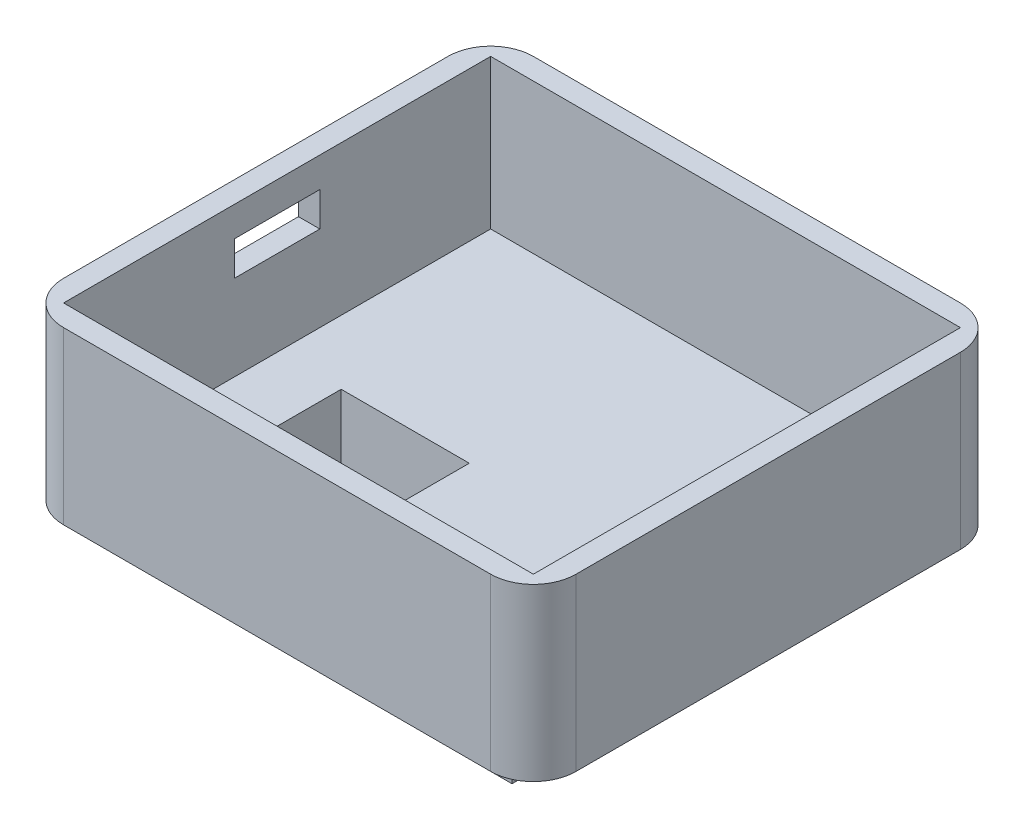
SolidWorks part; units mm, degrees
ref_plane "Front Plane" through (0, 0, 0) normal (0, 0, 1) x (1, 0, 0)
ref_plane "Top Plane" through (0, 0, 0) normal (0, 1, 0) x (1, 0, 0)
ref_plane "Right Plane" through (0, 0, 0) normal (1, 0, 0) x (0, 0, -1)
sketch "Sketch5" plane through (0, 0, 0) normal (0, 1, 0) x (1, 0, 0)
  line L0 (-30, 27.5) -> (30, -27.5) construction
  line L1 (-30, 27.5) -> (30, 27.5)
  line L2 (-30, 27.5) -> (-30, -27.5)
  line L3 (-30, -27.5) -> (30, -27.5)
  line L4 (30, 27.5) -> (30, -27.5)
  line L5 (30, 27.5) -> (-30, -27.5) construction
  point P4 (0, 0)
  dimension "D1" = 60
  dimension "D2" = 55
extrude "Boss-Extrude4" add sketch "Sketch5" along normal blind 20
sketch "Sketch6" plane through (0, 20, 0) normal (0, 1, 0) x (1, 0, 0)
  line L0 (-27.5, 25) -> (27.5, -25) construction
  line L1 (-27.5, 25) -> (27.5, 25)
  line L2 (-27.5, 25) -> (-27.5, -25)
  line L3 (-27.5, -25) -> (27.5, -25)
  line L4 (27.5, 25) -> (27.5, -25)
  line L5 (-27.5, -25) -> (27.5, 25) construction
  point P4 (0, 0)
  dimension "D1" = 55
  dimension "D2" = 50
extrude "Cut-Extrude2" cut sketch "Sketch6" against normal blind 17.5
fillet "Fillet1" radius 5 4 edges at (-30, 10, 27.5) (-30, 10, -27.5) (30, 10, -27.5) (30, 10, 27.5)
sketch "Sketch8" plane through (0, 0, 0) normal (0, -1, 0) x (1, 0, 0)
  line L0 (-22.5, 22.5) -> (22.5, -22.5) construction
  line L1 (-22.5, 22.5) -> (22.5, 22.5)
  line L2 (-22.5, 22.5) -> (-22.5, -22.5)
  line L3 (-22.5, -22.5) -> (22.5, -22.5)
  line L4 (22.5, 22.5) -> (22.5, -22.5)
  line L5 (22.5, 22.5) -> (-22.5, -22.5) construction
  point P4 (0, 0)
  dimension "D1" = 45
  dimension "D2" = 45
extrude "Boss-Extrude5" add sketch "Sketch8" along normal blind 5
sketch "Sketch9" plane through (0, -5, 0) normal (0, -1, 0) x (1, 0, 0)
  line L0 (22.5, 22.5) -> (-22.5, 22.5) construction
  line L1 (-20, 20) -> (-5, 20)
  line L2 (-20, 20) -> (-20, 0)
  line L3 (-20, 0) -> (-5, 0)
  line L4 (-5, 20) -> (-5, 0)
  line L5 (-22.5, 22.5) -> (-22.5, -22.5) construction
  dimension "D1" = 2.5
  dimension "D2" = 2.5
  dimension "D3" = 15
  dimension "D4" = 20
extrude "Cut-Extrude4" cut sketch "Sketch9" against normal up to next
sketch "Sketch11" plane through (-27.5, 0, 0) normal (1, 0, 0) x (0, 0, -1)
  line L0 (-25, 2.5) -> (-25, 20) construction
  line L1 (-5, 16.5) -> (5, 16.5)
  line L2 (-5, 16.5) -> (-5, 12.5)
  line L3 (-5, 12.5) -> (5, 12.5)
  line L4 (5, 16.5) -> (5, 12.5)
  line L5 (25, 2.5) -> (25, 20) construction
  line L6 (25, 2.5) -> (-25, 2.5) construction
  dimension "D1" = 20
  dimension "D2" = 20
  dimension "D3" = 10
  dimension "D4" = 4
extrude "Cut-Extrude5" cut sketch "Sketch11" against normal up to next
